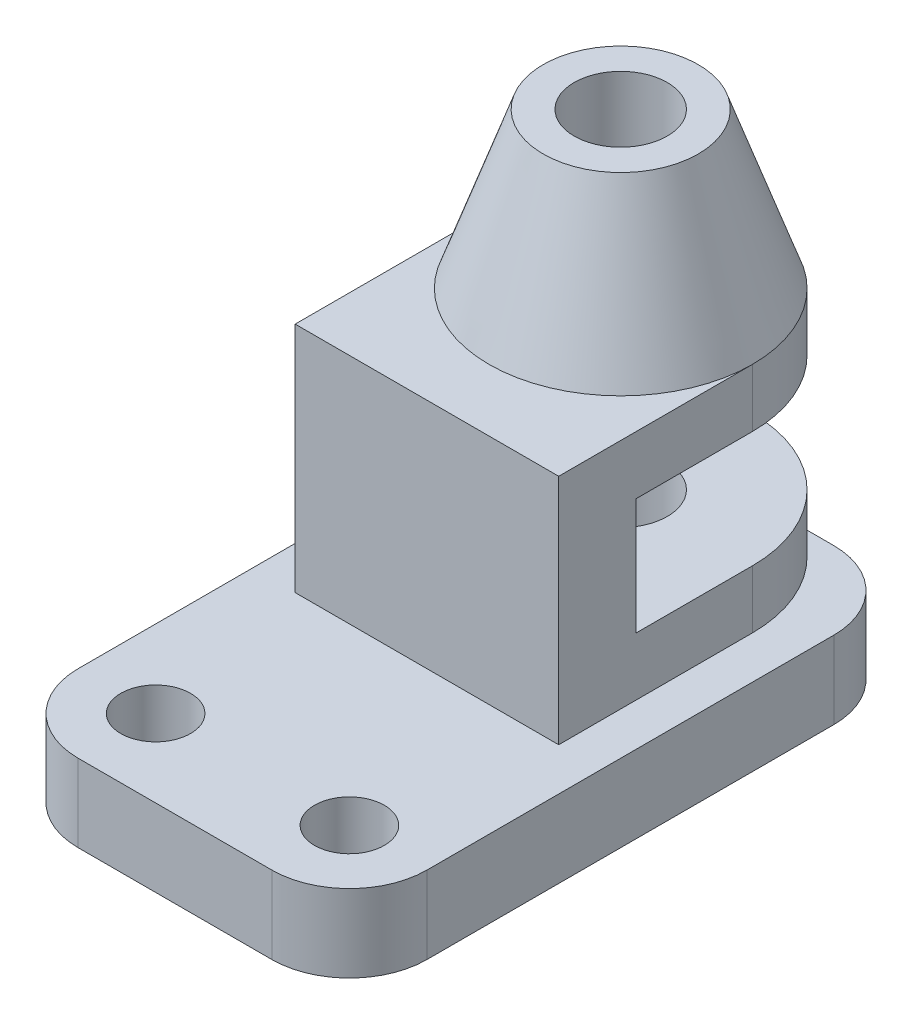
SolidWorks part; units mm, degrees
ref_plane "Front Plane" through (0, 0, 0) normal (0, 0, 1) x (1, 0, 0)
ref_plane "Top Plane" through (0, 0, 0) normal (0, 1, 0) x (1, 0, 0)
ref_plane "Right Plane" through (0, 0, 0) normal (1, 0, 0) x (0, 0, -1)
sketch "Sketch1" plane through (0, 0, 0) normal (0, 1, 0) x (1, 0, 0)
  line L1 (-25, -72.5) -> (25, -72.5)
  line L2 (-45, -52.5) -> (-45, 52.5)
  line L3 (-25, 72.5) -> (25, 72.5)
  line L4 (45, -52.5) -> (45, 52.5)
  line L5 (-45, -72.5) -> (45, 72.5) construction
  line L6 (-45, 72.5) -> (45, -72.5) construction
  arc A0 (45, 52.5) -> (25, 72.5) centre (25, 52.5) ccw
  arc A1 (-25, 72.5) -> (-45, 52.5) centre (-25, 52.5) ccw
  arc A2 (-25, -72.5) -> (-45, -52.5) centre (-25, -52.5) cw
  arc A3 (45, -52.5) -> (25, -72.5) centre (25, -52.5) cw
  circle A4 centre (25, -52.5) radius 9
  circle A5 centre (-25, -52.5) radius 9
  point P0 (0, 0)
  dimension "D3" = 20
  dimension "D5" = 18
  dimension "D1" = 145
  dimension "D2" = 90
  dimension "D4" = 50
extrude "Boss-Extrude1" add sketch "Sketch1" along normal blind 20
sketch "Sketch4" plane through (0, 20, 0) normal (0, 1, 0) x (1, 0, 0)
  line L0 (-34, -7.5) -> (34, -7.5)
  line L1 (34, -7.5) -> (34, 42.5)
  line L2 (-34, 42.5) -> (-34, -7.5)
  line L3 (-25, -72.5) -> (25, -72.5) construction
  line L4 (0, 0) -> (0, -7.5) construction
  arc A0 (34, 42.5) -> (-34, 42.5) centre (0, 42.5) ccw
  dimension "D1" = 65
  dimension "D2" = 68
  dimension "D3" = 50
extrude "Boss-Extrude4" add sketch "Sketch4" along normal blind 60 contours L0 L1 A0 L2
sketch "Sketch6" plane through (0, 80, 0) normal (0, 1, 0) x (1, 0, 0)
  line L0 (-34, 12.5) -> (34, 12.5)
  line L3 (-34, -7.5) -> (34, -7.5) construction
  line L7 (-34, 42.5) -> (-34, -7.5)
  line L8 (-34, -7.5) -> (34, -7.5)
  line L9 (34, -7.5) -> (34, 42.5)
  line L10 (-34, 42.5) -> (-34, 12.5)
  line L12 (34, 12.5) -> (34, 42.5)
  arc A1 (34, 42.5) -> (-34, 42.5) centre (0, 42.5) ccw
  arc A2 (34, 42.5) -> (-34, 42.5) centre (0, 42.5) ccw
  point P6 (0, 0)
  dimension "D1" = 20
  dimension "D2" = 0
extrude "Cut-Extrude1" cut sketch "Sketch6" against normal blind 30 from offset 15 offset against normal yes
ref_plane "Plane2" through (0, 0, -42.5) normal (0, 0, 1) x (1, 0, 0)
sketch "Sketch7" plane through (0, 0, -42.5) normal (0, 0, 1) x (1, 0, 0)
  line L0 (0, 80) -> (0, 120) construction
  line L1 (-34, 80) -> (34, 80) construction
  line L2 (0, 120) -> (20, 120)
  line L3 (0, 80) -> (34, 80)
  line L4 (34, 80) -> (20, 120)
  line L5 (0, 80) -> (0, 120)
  dimension "D1" = 20
  dimension "D2" = 34
  dimension "D3" = 40
revolve "Revolve1" add sketch "Sketch7" angle 360 about L5
sketch "Sketch9" plane through (0, 120, 0) normal (0, 1, 0) x (1, 0, 0)
  circle A0 centre (0, 42.5) radius 12
  dimension "D1" = 24
extrude "Cut-Extrude2" cut sketch "Sketch9" against normal through all
